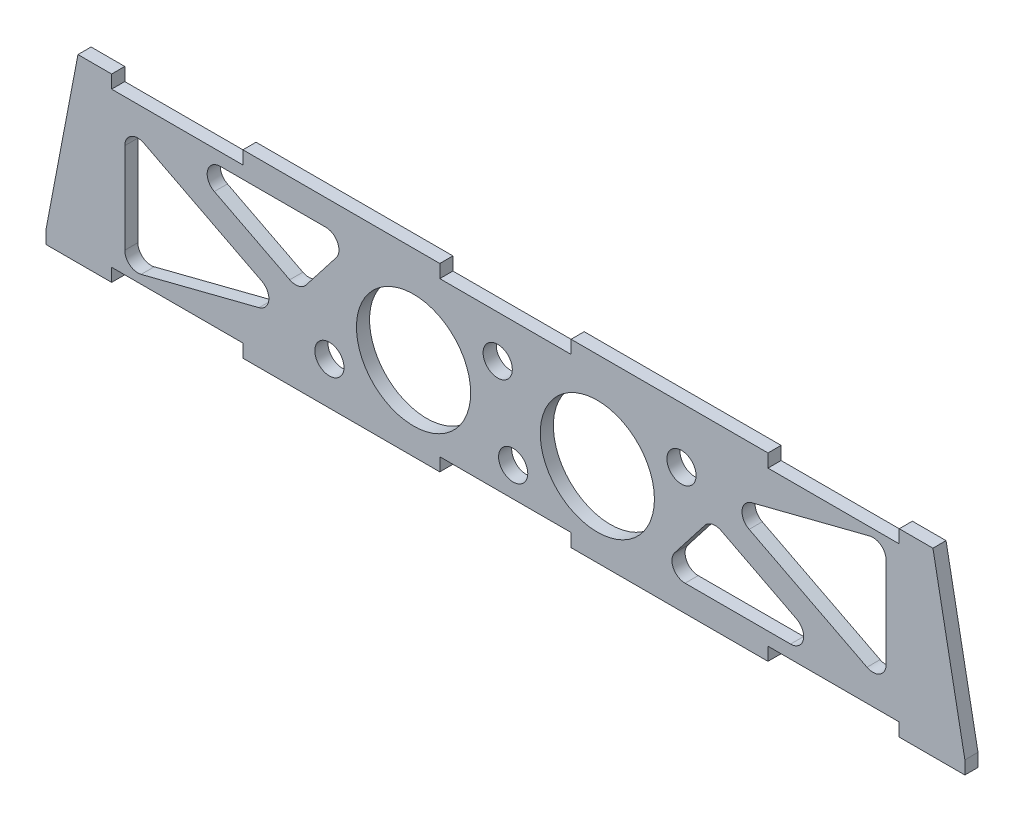
SolidWorks part; units mm, degrees
material "AISI 4340 Steel, normalized"
ref_plane "Front Plane" through (0, 0, 0) normal (0, 0, 1) x (1, 0, 0)
ref_plane "Top Plane" through (0, 0, 0) normal (0, 1, 0) x (1, 0, 0)
ref_plane "Right Plane" through (0, 0, 0) normal (1, 0, 0) x (0, 0, -1)
sketch "Sketch1" plane through (0, 0, 0) normal (0, 0, 1) x (1, 0, 0)
  line B0 (11.4917, -5.8968) -> (-11.4917, 5.8968)
  line B1 (-22.481, -13.4556) -> (9.6655, -13.4556)
  line B2 (-16.4765, 4.7922) -> (-25.6397, -7.0015)
  line B3 (53.0447, 33.5444) -> (-207.487, 33.5444)
  line B4 (-207.487, 33.5444) -> (-217.2211, -17.4556)
  line B5 (-217.2211, -17.4556) -> (-217.2211, -21.4556)
  line B6 (-217.2211, -21.4556) -> (62.7789, -21.4556)
  line B7 (62.7789, -21.4556) -> (62.7789, -17.4556)
  line B8 (62.7789, -17.4556) -> (53.0447, 33.5444)
  line B9 (38.7789, -4.3587) -> (38.7789, 23.244)
  line B10 (33.7889, 27.1195) -> (-2.1251, 17.9457)
  line B11 (-2.9613, 10.5113) -> (32.9527, -7.9176)
  line B12 (-165.9339, 18.1773) -> (-142.9506, 6.3837)
  line B13 (-131.9612, 25.7361) -> (-164.1077, 25.7361)
  line B14 (-137.9658, 7.4883) -> (-128.8025, 19.2819)
  line B15 (-188.2311, -14.8391) -> (-152.3171, -5.6652)
  line B16 (-151.4809, 1.7691) -> (-187.395, 20.198)
  line B17 (-193.2211, 16.6392) -> (-193.2211, -10.9635)
  arc B18 (-11.4917, 5.8968) -> (-16.4765, 4.7922) centre (-13.3178, 2.338) ccw
  arc B19 (9.6655, -13.4556) -> (11.4917, -5.8968) centre (9.6655, -9.4556) ccw
  arc B20 (-25.6397, -7.0015) -> (-22.481, -13.4556) centre (-22.481, -9.4556) ccw
  circle B21 centre (-23.5774, 16.5944) radius 4.45
  circle B22 centre (-49.2211, 4.0444) radius 17.4
  circle B23 centre (-74.8648, -8.5056) radius 4.45
  circle B24 centre (-79.5774, 16.5944) radius 4.45
  circle B25 centre (-130.8648, -8.5056) radius 4.45
  circle B26 centre (-105.2211, 4.0444) radius 17.4
  arc B27 (32.9527, -7.9176) -> (38.7789, -4.3587) centre (34.7789, -4.3587) ccw
  arc B28 (38.7789, 23.244) -> (33.7889, 27.1195) centre (34.7789, 23.244) ccw
  arc B29 (-2.1251, 17.9457) -> (-2.9613, 10.5113) centre (-1.1351, 14.0701) ccw
  arc B30 (-142.9506, 6.3837) -> (-137.9658, 7.4883) centre (-141.1244, 9.9425) ccw
  arc B31 (-128.8025, 19.2819) -> (-131.9612, 25.7361) centre (-131.9612, 21.7361) ccw
  arc B32 (-164.1077, 25.7361) -> (-165.9339, 18.1773) centre (-164.1077, 21.7361) ccw
  arc B33 (-193.2211, -10.9635) -> (-188.2311, -14.8391) centre (-189.2211, -10.9635) ccw
  arc B34 (-152.3171, -5.6652) -> (-151.4809, 1.7691) centre (-153.3071, -1.7897) ccw
  arc B35 (-187.395, 20.198) -> (-193.2211, 16.6392) centre (-189.2211, 16.6392) ccw
sketch_block_instance "Block-base front-1"
sketch_block "Block-base front"
sketch "Sketch2" plane through (0, 0, 0) normal (0, 0, 1) x (1, 0, 0)
  line L0 (53.0447, 33.5444) -> (-207.487, 33.5444) construction
  line L1 (-207.487, 33.5444) -> (-217.2211, -17.4556) construction
  line L2 (-217.2211, -17.4556) -> (-217.2211, -21.4556) construction
  line L3 (-217.2211, -21.4556) -> (62.7789, -21.4556) construction
  line L4 (62.7789, -21.4556) -> (62.7789, -17.4556) construction
  line L5 (62.7789, -17.4556) -> (53.0447, 33.5444) construction
  line L6 (-16.4765, 4.7922) -> (-25.6397, -7.0015) construction
  line L7 (11.4917, -5.8968) -> (-11.4917, 5.8968) construction
  line L8 (-22.481, -13.4556) -> (9.6655, -13.4556) construction
  line L9 (-165.9339, 18.1773) -> (-142.9506, 6.3837) construction
  line L10 (-137.9658, 7.4883) -> (-128.8025, 19.2819) construction
  line L11 (-131.9612, 25.7361) -> (-164.1077, 25.7361) construction
  line L12 (38.7789, -4.3587) -> (38.7789, 23.244) construction
  line L13 (-2.9613, 10.5113) -> (32.9527, -7.9176) construction
  line L14 (33.7889, 27.1195) -> (-2.1251, 17.9457) construction
  line L15 (-188.2311, -14.8391) -> (-152.3171, -5.6652) construction
  line L16 (-151.4809, 1.7691) -> (-187.395, 20.198) construction
  line L17 (-193.2211, 16.6392) -> (-193.2211, -10.9635) construction
  line L18 (53.0447, 33.5444) -> (42.7789, 33.5444)
  line L19 (-207.487, 33.5444) -> (-217.2211, -17.4556)
  line L20 (-217.2211, -17.4556) -> (-217.2211, -21.4556)
  line L21 (-217.2211, -21.4556) -> (-197.2211, -21.4556)
  line L22 (62.7789, -21.4556) -> (62.7789, -17.4556)
  line L23 (62.7789, -17.4556) -> (53.0447, 33.5444)
  line L24 (-16.4765, 4.7922) -> (-25.6397, -7.0015)
  line L25 (11.4917, -5.8968) -> (-11.4917, 5.8968)
  line L26 (-22.481, -13.4556) -> (9.6655, -13.4556)
  line L27 (-165.9339, 18.1773) -> (-142.9506, 6.3837)
  line L28 (-137.9658, 7.4883) -> (-128.8025, 19.2819)
  line L29 (-131.9612, 25.7361) -> (-164.1077, 25.7361)
  line L30 (38.7789, -4.3587) -> (38.7789, 23.244)
  line L31 (-2.9613, 10.5113) -> (32.9527, -7.9176)
  line L32 (33.7889, 27.1195) -> (-2.1251, 17.9457)
  line L33 (-188.2311, -14.8391) -> (-152.3171, -5.6652)
  line L34 (-151.4809, 1.7691) -> (-187.395, 20.198)
  line L35 (-193.2211, 16.6392) -> (-193.2211, -10.9635)
  line L36 (-77.2211, -21.4556) -> (-77.2211, 33.5444) construction
  line L37 (-57.2211, -17.4556) -> (-97.2211, -17.4556)
  line L38 (-97.2211, -17.4556) -> (-97.2211, -21.4556)
  line L39 (-157.2211, -21.4556) -> (-157.2211, -17.4556)
  line L40 (-157.2211, -17.4556) -> (-197.2211, -17.4556)
  line L41 (-197.2211, -17.4556) -> (-197.2211, -21.4556)
  line L42 (-57.2211, -17.4556) -> (-57.2211, -21.4556)
  line L43 (42.7789, -17.4556) -> (42.7789, -21.4556)
  line L44 (2.7789, -17.4556) -> (42.7789, -17.4556)
  line L45 (2.7789, -21.4556) -> (2.7789, -17.4556)
  line L46 (-157.2211, -21.4556) -> (-97.2211, -21.4556)
  line L47 (-57.2211, -21.4556) -> (2.7789, -21.4556)
  line L48 (42.7789, -21.4556) -> (62.7789, -21.4556)
  line L49 (-77.2211, 6.0444) -> (-212.7358, 6.0444) construction
  line L50 (42.7789, 29.5444) -> (42.7789, 33.5444)
  line L51 (2.7789, 29.5444) -> (42.7789, 29.5444)
  line L52 (2.7789, 33.5444) -> (2.7789, 29.5444)
  line L53 (-57.2211, 29.5444) -> (-57.2211, 33.5444)
  line L54 (-57.2211, 29.5444) -> (-97.2211, 29.5444)
  line L55 (-97.2211, 29.5444) -> (-97.2211, 33.5444)
  line L56 (-197.2211, 29.5444) -> (-197.2211, 33.5444)
  line L57 (-157.2211, 29.5444) -> (-197.2211, 29.5444)
  line L58 (-157.2211, 33.5444) -> (-157.2211, 29.5444)
  line L59 (-197.2211, 33.5444) -> (-207.487, 33.5444)
  line L60 (-97.2211, 33.5444) -> (-157.2211, 33.5444)
  line L61 (2.7789, 33.5444) -> (-57.2211, 33.5444)
  circle A0 centre (-105.2211, 4.0444) radius 17.4 construction
  circle A1 centre (-130.8648, -8.5056) radius 4.45 construction
  circle A2 centre (-79.5774, 16.5944) radius 4.45 construction
  circle A3 centre (-74.8648, -8.5056) radius 4.45 construction
  circle A4 centre (-49.2211, 4.0444) radius 17.4 construction
  circle A5 centre (-23.5774, 16.5944) radius 4.45 construction
  arc A6 (-11.4917, 5.8968) -> (-16.4765, 4.7922) centre (-13.3178, 2.338) ccw construction
  arc A7 (9.6655, -13.4556) -> (11.4917, -5.8968) centre (9.6655, -9.4556) ccw construction
  arc A8 (-25.6397, -7.0015) -> (-22.481, -13.4556) centre (-22.481, -9.4556) ccw construction
  arc A9 (-142.9506, 6.3837) -> (-137.9658, 7.4883) centre (-141.1244, 9.9425) ccw construction
  arc A10 (-128.8025, 19.2819) -> (-131.9612, 25.7361) centre (-131.9612, 21.7361) ccw construction
  arc A11 (-164.1077, 25.7361) -> (-165.9339, 18.1773) centre (-164.1077, 21.7361) ccw construction
  arc A12 (32.9527, -7.9176) -> (38.7789, -4.3587) centre (34.7789, -4.3587) ccw construction
  arc A13 (-2.1251, 17.9457) -> (-2.9613, 10.5113) centre (-1.1351, 14.0701) ccw construction
  arc A14 (38.7789, 23.244) -> (33.7889, 27.1195) centre (34.7789, 23.244) ccw construction
  arc A15 (-152.3171, -5.6652) -> (-151.4809, 1.7691) centre (-153.3071, -1.7897) ccw construction
  arc A16 (-187.395, 20.198) -> (-193.2211, 16.6392) centre (-189.2211, 16.6392) ccw construction
  arc A17 (-193.2211, -10.9635) -> (-188.2311, -14.8391) centre (-189.2211, -10.9635) ccw construction
  circle A18 centre (-105.2211, 4.0444) radius 17.4
  circle A19 centre (-130.8648, -8.5056) radius 4.45
  circle A20 centre (-79.5774, 16.5944) radius 4.45
  circle A21 centre (-74.8648, -8.5056) radius 4.45
  circle A22 centre (-49.2211, 4.0444) radius 17.4
  circle A23 centre (-23.5774, 16.5944) radius 4.45
  arc A24 (-11.4917, 5.8968) -> (-16.4765, 4.7922) centre (-13.3178, 2.338) ccw
  arc A25 (9.6655, -13.4556) -> (11.4917, -5.8968) centre (9.6655, -9.4556) ccw
  arc A26 (-25.6397, -7.0015) -> (-22.481, -13.4556) centre (-22.481, -9.4556) ccw
  arc A27 (-142.9506, 6.3837) -> (-137.9658, 7.4883) centre (-141.1244, 9.9425) ccw
  arc A28 (-128.8025, 19.2819) -> (-131.9612, 25.7361) centre (-131.9612, 21.7361) ccw
  arc A29 (-164.1077, 25.7361) -> (-165.9339, 18.1773) centre (-164.1077, 21.7361) ccw
  arc A30 (32.9527, -7.9176) -> (38.7789, -4.3587) centre (34.7789, -4.3587) ccw
  arc A31 (-2.1251, 17.9457) -> (-2.9613, 10.5113) centre (-1.1351, 14.0701) ccw
  arc A32 (38.7789, 23.244) -> (33.7889, 27.1195) centre (34.7789, 23.244) ccw
  arc A33 (-152.3171, -5.6652) -> (-151.4809, 1.7691) centre (-153.3071, -1.7897) ccw
  arc A34 (-187.395, 20.198) -> (-193.2211, 16.6392) centre (-189.2211, 16.6392) ccw
  arc A35 (-193.2211, -10.9635) -> (-188.2311, -14.8391) centre (-189.2211, -10.9635) ccw
  point P70 (-157.2211, -19.4556)
  point P72 (-77.2211, -17.4556)
  dimension "D1" = 40
  dimension "D2" = 20
  dimension "D3" = 60
extrude "Boss-Extrude1" add sketch "Sketch2" along normal blind 4
